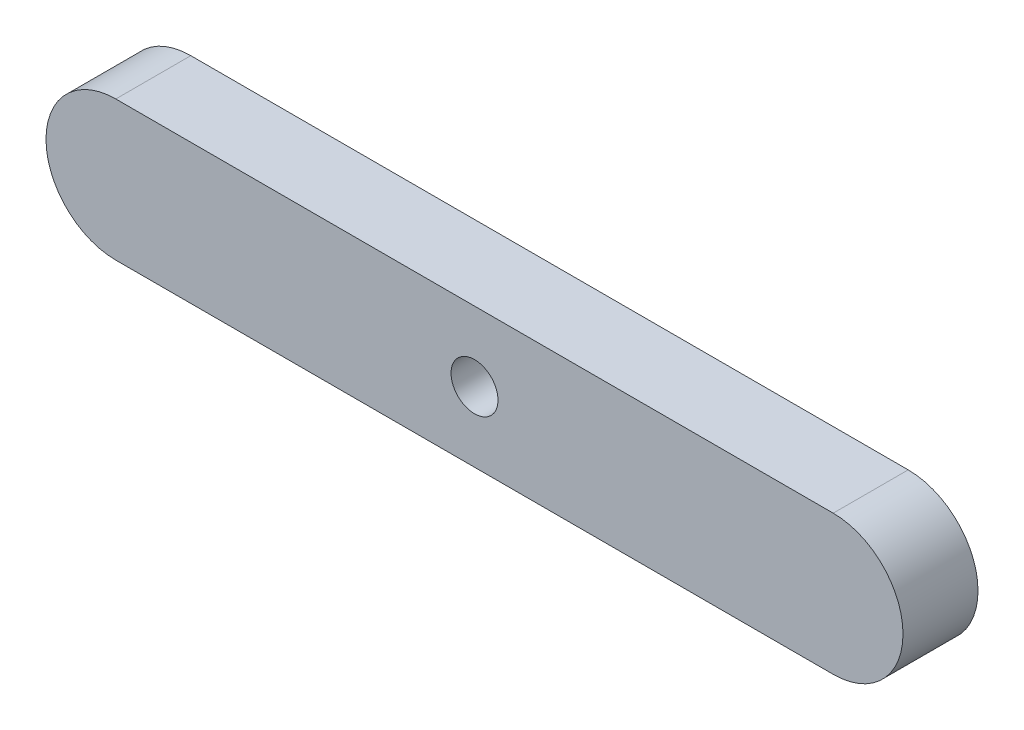
SolidWorks part; units mm, degrees
ref_plane "Front Plane" through (0, 0, 0) normal (0, 0, 1) x (1, 0, 0)
ref_plane "Top Plane" through (0, 0, 0) normal (0, 1, 0) x (1, 0, 0)
ref_plane "Right Plane" through (0, 0, 0) normal (1, 0, 0) x (0, 0, -1)
sketch "Sketch1" plane through (0, 0, 0) normal (0, 0, 1) x (1, 0, 0)
  line L0 (41.1169, 0) -> (-54.5339, 0) construction
  line L1 (41.1169, -9.3054) -> (-54.5339, -9.3054)
  line L2 (41.1169, 9.3054) -> (-54.5339, 9.3054)
  arc A0 (41.1169, -9.3054) -> (41.1169, 9.3054) centre (41.1169, 0) ccw
  arc A1 (-54.5339, 9.3054) -> (-54.5339, -9.3054) centre (-54.5339, 0) ccw
  point P3 (-6.7085, 0)
extrude "Boss-Extrude1" add sketch "Sketch1" along normal blind 10
sketch "Sketch2" plane through (0, 0, 10) normal (0, 0, 1) x (1, 0, 0)
  line L0 (41.1169, 0) -> (-54.5339, 0) construction
  circle A0 centre (-6.7085, 0) radius 3.1297
extrude "Cut-Extrude1" cut sketch "Sketch2" against normal blind 24
